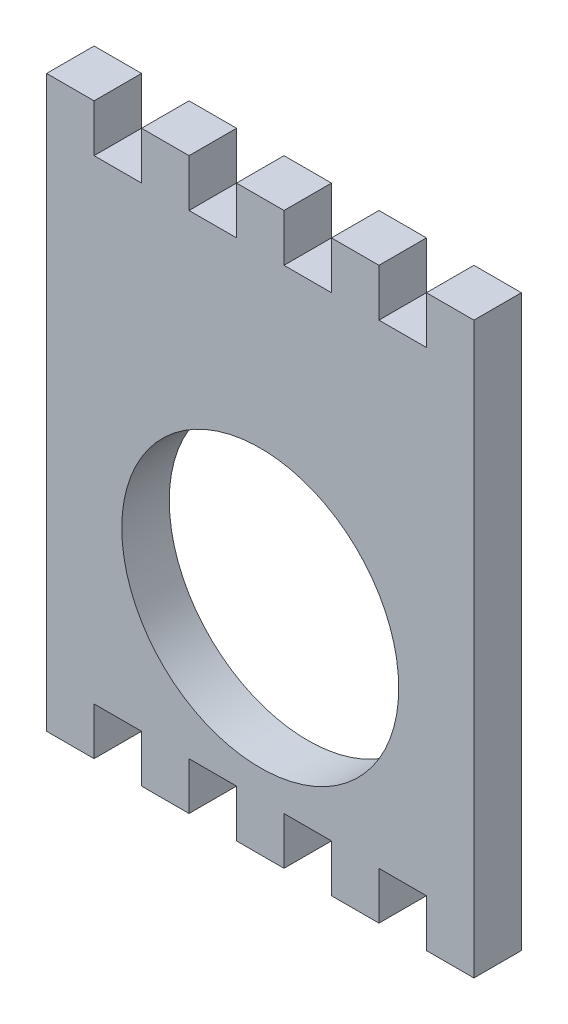
SolidWorks part; units mm, degrees
ref_plane "Front Plane" through (0, 0, 0) normal (0, 0, 1) x (1, 0, 0)
ref_plane "Top Plane" through (0, 0, 0) normal (0, 1, 0) x (1, 0, 0)
ref_plane "Right Plane" through (0, 0, 0) normal (1, 0, 0) x (0, 0, -1)
sketch "Sketch1" plane through (0, 0, 0) normal (0, 0, 1) x (1, 0, 0)
  line L0 (-20.3297, 36.6528) -> (-20.3297, 0.6528) construction
  line L1 (-33.8297, 43.3803) -> (-30.8297, 43.3803)
  line L2 (-33.8297, 43.3803) -> (-33.8297, 7.3803)
  line L3 (-33.8297, 7.3803) -> (-30.8297, 7.3803)
  line L4 (-6.8297, 43.3803) -> (-6.8297, 7.3803)
  line L5 (-33.8297, 25.3803) -> (-6.8297, 25.3803) construction
  line L6 (-24.8297, 10.3803) -> (-21.8297, 10.3803)
  line L7 (-30.8297, 10.3803) -> (-27.8297, 10.3803)
  line L8 (-30.8297, 10.3803) -> (-30.8297, 7.3803)
  line L10 (-27.8297, 10.3803) -> (-27.8297, 7.3803)
  line L11 (-24.8297, 10.3803) -> (-24.8297, 7.3803)
  line L13 (-21.8297, 10.3803) -> (-21.8297, 7.3803)
  line L14 (-15.8297, 10.3803) -> (-15.8297, 7.3803)
  line L16 (-18.8297, 10.3803) -> (-18.8297, 7.3803)
  line L17 (-15.8297, 10.3803) -> (-18.8297, 10.3803)
  line L19 (-12.8297, 10.3803) -> (-12.8297, 7.3803)
  line L20 (-9.8297, 10.3803) -> (-12.8297, 10.3803)
  line L21 (-9.8297, 10.3803) -> (-9.8297, 7.3803)
  line L22 (-9.8297, 40.3803) -> (-9.8297, 43.3803)
  line L23 (-9.8297, 40.3803) -> (-12.8297, 40.3803)
  line L24 (-12.8297, 40.3803) -> (-12.8297, 43.3803)
  line L26 (-15.8297, 40.3803) -> (-18.8297, 40.3803)
  line L27 (-18.8297, 40.3803) -> (-18.8297, 43.3803)
  line L29 (-15.8297, 40.3803) -> (-15.8297, 43.3803)
  line L30 (-24.8297, 40.3803) -> (-24.8297, 43.3803)
  line L32 (-21.8297, 40.3803) -> (-21.8297, 43.3803)
  line L33 (-24.8297, 40.3803) -> (-21.8297, 40.3803)
  line L35 (-27.8297, 40.3803) -> (-27.8297, 43.3803)
  line L36 (-30.8297, 40.3803) -> (-27.8297, 40.3803)
  line L37 (-30.8297, 40.3803) -> (-30.8297, 43.3803)
  line L38 (-27.8297, 7.3803) -> (-24.8297, 7.3803)
  line L39 (-21.8297, 7.3803) -> (-18.8297, 7.3803)
  line L40 (-15.8297, 7.3803) -> (-12.8297, 7.3803)
  line L41 (-9.8297, 7.3803) -> (-6.8297, 7.3803)
  line L42 (-27.8297, 43.3803) -> (-24.8297, 43.3803)
  line L43 (-21.8297, 43.3803) -> (-18.8297, 43.3803)
  line L44 (-15.8297, 43.3803) -> (-12.8297, 43.3803)
  line L45 (-9.8297, 43.3803) -> (-6.8297, 43.3803)
  circle A0 centre (-20.3297, 20.8803) radius 8.75
  point P42 (0, 0)
  dimension "D5" = 17.5
  dimension "D1" = 27
  dimension "D2" = 36
  dimension "D3" = 3
  dimension "D4" = 3
  dimension "D6" = 3
  dimension "D7" = 3
  dimension "D8" = 3
  dimension "D9" = 0
  dimension "D10" = 3
  dimension "D11" = 10.5
extrude "Boss-Extrude1" add sketch "Sketch1" along normal blind 3
